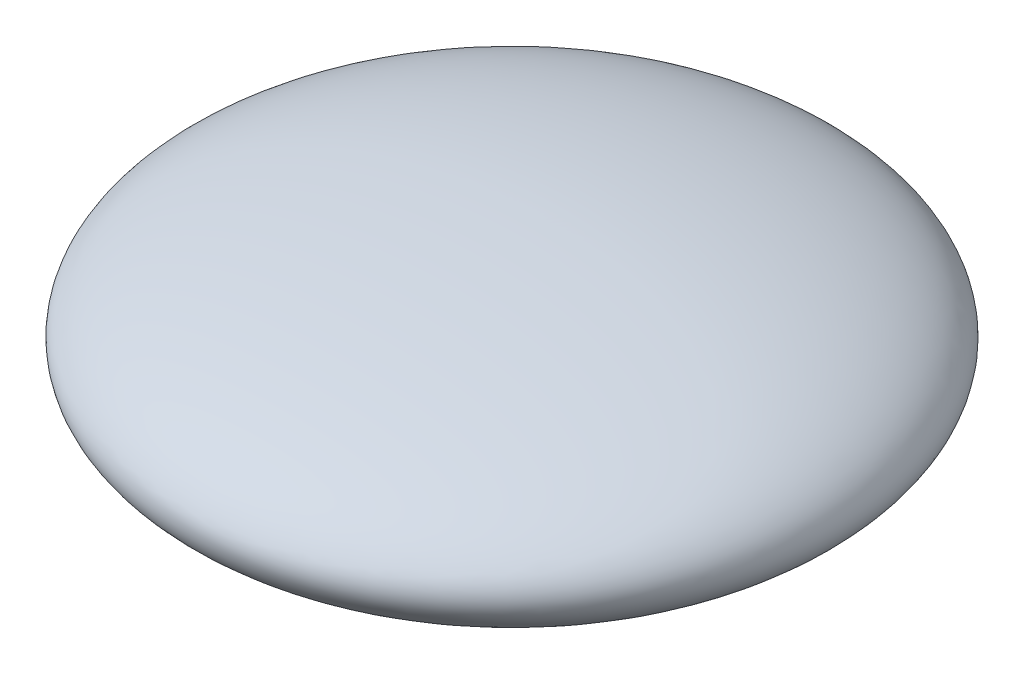
SolidWorks part; units mm, degrees
material "Plain Carbon Steel"
ref_plane "Front Plane" through (0, 0, 0) normal (0, 0, 1) x (1, 0, 0)
ref_plane "Top Plane" through (0, 0, 0) normal (0, 1, 0) x (1, 0, 0)
ref_plane "Right Plane" through (0, 0, 0) normal (1, 0, 0) x (0, 0, -1)
sketch "Sketch1" plane through (0, 0, 0) normal (0, 0, 1) x (1, 0, 0)
  line L8 (0, 0) -> (0, 14.3)
  line L9 (0, 0) -> (14.85, 0)
  line L11 (14.85, 0) -> (21.733, 3.5)
  line L12 (55, 0) -> (-55, 0) construction
  line L13 (0, -55) -> (0, 55) construction
  ellipse E0 centre (0, 7.0723) end of major axis (25, 7.0723) minor radius 7.2277 (21.733, 3.5) -> (0, 14.3) ccw
  point P4 (26.9169, 6.136)
  dimension "D1" = 14.3
  dimension "D2" = 14.85
  dimension "D3" = 25
  dimension "D4" = 3.5
revolve "Revolve3" add sketch "Sketch1" angle 360 about L8
